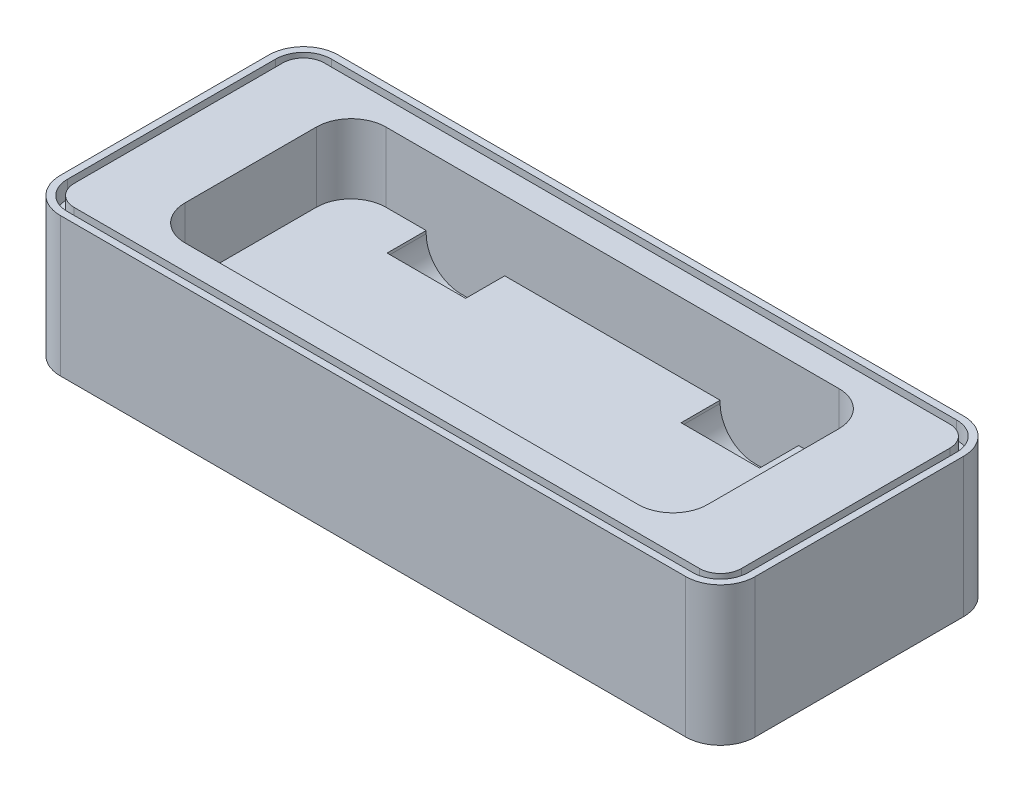
SolidWorks part; units mm, degrees
other "Camera1"
ref_plane "Front Plane" through (0, 0, 0) normal (0, 0, 1) x (1, 0, 0)
ref_plane "Top Plane" through (0, 0, 0) normal (0, 1, 0) x (1, 0, 0)
ref_plane "Right Plane" through (0, 0, 0) normal (1, 0, 0) x (0, 0, -1)
sketch "Sketch1" plane through (0, 0, 0) normal (0, 0, 1) x (1, 0, 0)
  line L1 (0, 0) -> (10, 0)
  line L2 (0, 0) -> (0, -2)
  line L3 (0, -2) -> (10, -2)
  line L4 (10, 0) -> (10, -2)
  dimension "D1" = 2
  dimension "D2" = 10
extrude "Boss-Extrude1" add sketch "Sketch1" against normal blind 4
sketch "Sketch2" plane through (0, 0, 0) normal (0, 1, 0) x (1, 0, 0)
  line L0 (10, 4) -> (0, 4) construction
  line L1 (1.24, 3.445) -> (8.76, 3.445)
  line L2 (1.24, 3.445) -> (1.24, 0.555)
  line L3 (1.24, 0.555) -> (8.76, 0.555)
  line L4 (8.76, 3.445) -> (8.76, 0.555)
  line L5 (1.24, 3.445) -> (8.76, 0.555) construction
  line L6 (1.24, 0.555) -> (8.76, 3.445) construction
  line L7 (10, 4) -> (10, 0) construction
  point P0 (5, 2)
  point P5 (0, 0)
  point P8 (5, 4)
  point P9 (0, 0)
  point P12 (10, 2)
  dimension "D1" = 7.52
  dimension "D2" = 2.89
extrude "Cut-Extrude1" cut sketch "Sketch2" against normal blind 1
fillet "Fillet1" radius 0.5 4 edges at (0, -1, -4) (0, -1, 0) (10, -1, -4) (10, -1, 0)
fillet "Fillet2" radius 0.5 4 edges at (1.24, -0.5, -0.555) (8.76, -0.5, -0.555) (8.76, -0.5, -3.445) (1.24, -0.5, -3.445)
sketch "Sketch5" plane through (0, -1, 0) normal (0, 1, 0) x (1, 0, 0)
  line L0 (8.26, 3.445) -> (1.74, 3.445) construction
  line L1 (2.32, 3.445) -> (3.45, 3.445)
  line L2 (2.32, 3.445) -> (2.32, 2.883)
  line L3 (2.32, 2.883) -> (3.45, 2.883)
  line L4 (3.45, 3.445) -> (3.45, 2.883)
  line L5 (5, -996) -> (5, 49004) construction
  line L6 (6.55, 3.445) -> (7.68, 3.445)
  line L7 (6.55, 3.445) -> (6.55, 2.883)
  line L8 (6.55, 2.883) -> (7.68, 2.883)
  line L9 (7.68, 3.445) -> (7.68, 2.883)
  line L10 (9.5, 4) -> (0.5, 4) construction
  line L11 (3.45, 2.883) -> (6.55, 2.883) construction
  line L12 (-990, 2) -> (49010, 2) construction
  line L13 (10, 3.5) -> (10, 0.5) construction
  line L14 (6.55, 1.117) -> (7.68, 1.117)
  line L15 (7.68, 0.555) -> (7.68, 1.117)
  line L16 (6.55, 0.555) -> (7.68, 0.555)
  line L17 (6.55, 0.555) -> (6.55, 1.117)
  line L18 (2.32, 1.117) -> (3.45, 1.117)
  line L19 (3.45, 0.555) -> (3.45, 1.117)
  line L20 (2.32, 0.555) -> (3.45, 0.555)
  line L21 (2.32, 0.555) -> (2.32, 1.117)
  point P11 (5, 2.883)
  point P15 (5, 4)
  point P21 (10, 2)
  dimension "D1" = 1.13
  dimension "D2" = 1.13
  dimension "D3" = 0.562
  dimension "D4" = 0.562
  dimension "D5" = 3.1
extrude "Cut-Extrude3" cut sketch "Sketch5" against normal blind 0.54
sketch "Sketch9" plane through (0, 0, 0) normal (0, 1, 0) x (1, 0, 0)
  line L20 (0.5, 0.2) -> (9.5, 0.2)
  line L21 (9.8, 0.5) -> (9.8, 3.5)
  line L22 (9.5, 3.8) -> (0.5, 3.8)
  line L23 (0.2, 3.5) -> (0.2, 0.5)
  line L24 (9.9, 0.5) -> (9.9, 3.5)
  line L25 (9.5, 3.9) -> (0.5, 3.9)
  line L26 (0.5, 0.1) -> (9.5, 0.1)
  line L27 (0.1, 3.5) -> (0.1, 0.5)
  line L28 (9.9, 0.5) -> (9.9, 3.5)
  line L29 (9.5, 3.9) -> (0.5, 3.9)
  line L30 (0.5, 0.1) -> (9.5, 0.1)
  line L31 (0.1, 3.5) -> (0.1, 0.5)
  arc A16 (9.5, 0.2) -> (9.8, 0.5) centre (9.5, 0.5) ccw
  arc A17 (9.8, 3.5) -> (9.5, 3.8) centre (9.5, 3.5) ccw
  arc A18 (0.5, 3.8) -> (0.2, 3.5) centre (0.5, 3.5) ccw
  arc A19 (0.2, 0.5) -> (0.5, 0.2) centre (0.5, 0.5) ccw
  arc A20 (9.5, 0.1) -> (9.9, 0.5) centre (9.5, 0.5) ccw
  arc A21 (9.9, 3.5) -> (9.5, 3.9) centre (9.5, 3.5) ccw
  arc A22 (0.5, 3.9) -> (0.1, 3.5) centre (0.5, 3.5) ccw
  arc A23 (0.1, 0.5) -> (0.5, 0.1) centre (0.5, 0.5) ccw
  arc A24 (9.5, 0.1) -> (9.9, 0.5) centre (9.5, 0.5) ccw
  arc A25 (9.9, 3.5) -> (9.5, 3.9) centre (9.5, 3.5) ccw
  arc A26 (0.5, 3.9) -> (0.1, 3.5) centre (0.5, 3.5) ccw
  arc A27 (0.1, 0.5) -> (0.5, 0.1) centre (0.5, 0.5) ccw
  dimension "D1" = 0.1
  dimension "D2" = 0.1
extrude "Cut-Extrude8" cut sketch "Sketch9" against normal blind 0.25
fillet "Fillet4" radius 0.5 8 edges at (7.68, -1.54, -3.164) (7.68, -1.54, -0.836) (6.55, -1.54, -3.164) (6.55, -1.54, -0.836) (3.45, -1.54, -0.836) (2.32, -1.54, -0.836) (3.45, -1.54, -3.164) (2.32, -1.54, -3.164)
